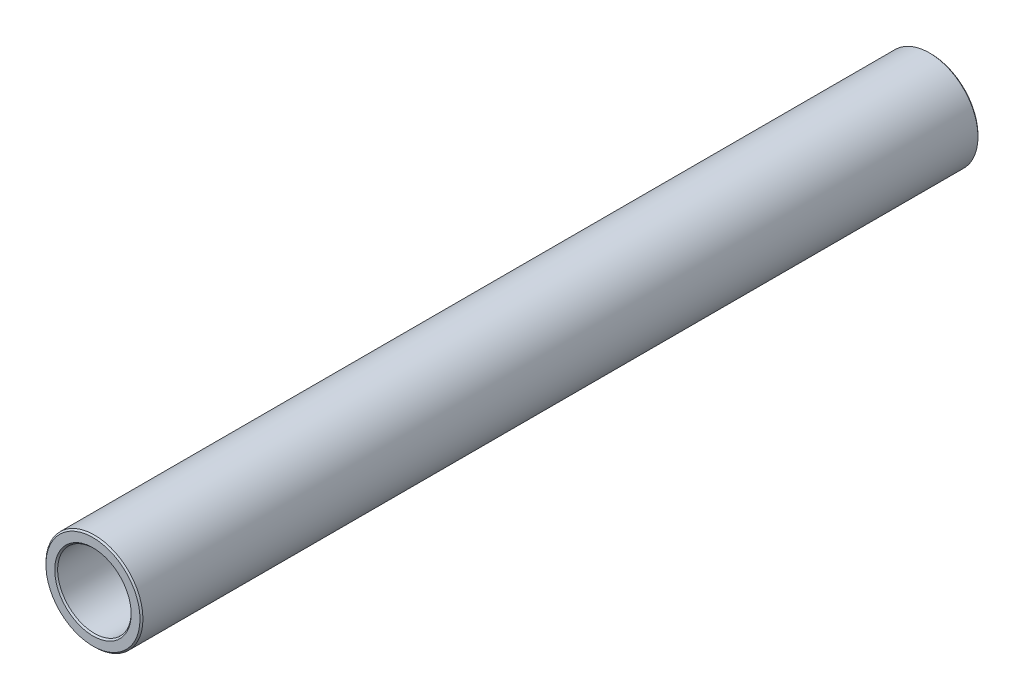
SolidWorks part; units mm, degrees
material "20"
ref_plane "前视基准面" through (0, 0, 0) normal (0, 0, 1) x (1, 0, 0)
ref_plane "上视基准面" through (0, 0, 0) normal (0, 1, 0) x (1, 0, 0)
ref_plane "右视基准面" through (0, 0, 0) normal (1, 0, 0) x (0, 0, -1)
sketch "草图1" plane through (0, 0, 0) normal (0, 0, 1) x (1, 0, 0)
  circle A0 centre (0, 0) radius 25
  circle A1 centre (0, 0) radius 33
  dimension "D1" = 50
  dimension "D2" = 66
extrude "凸台-拉伸1" add sketch "草图1" along normal mid plane 570
chamfer "倒角1" distance 1 angle 45 4 edges at (25, 0, 285) (33, 0, 285) (25, 0, -285) (33, 0, -285)
